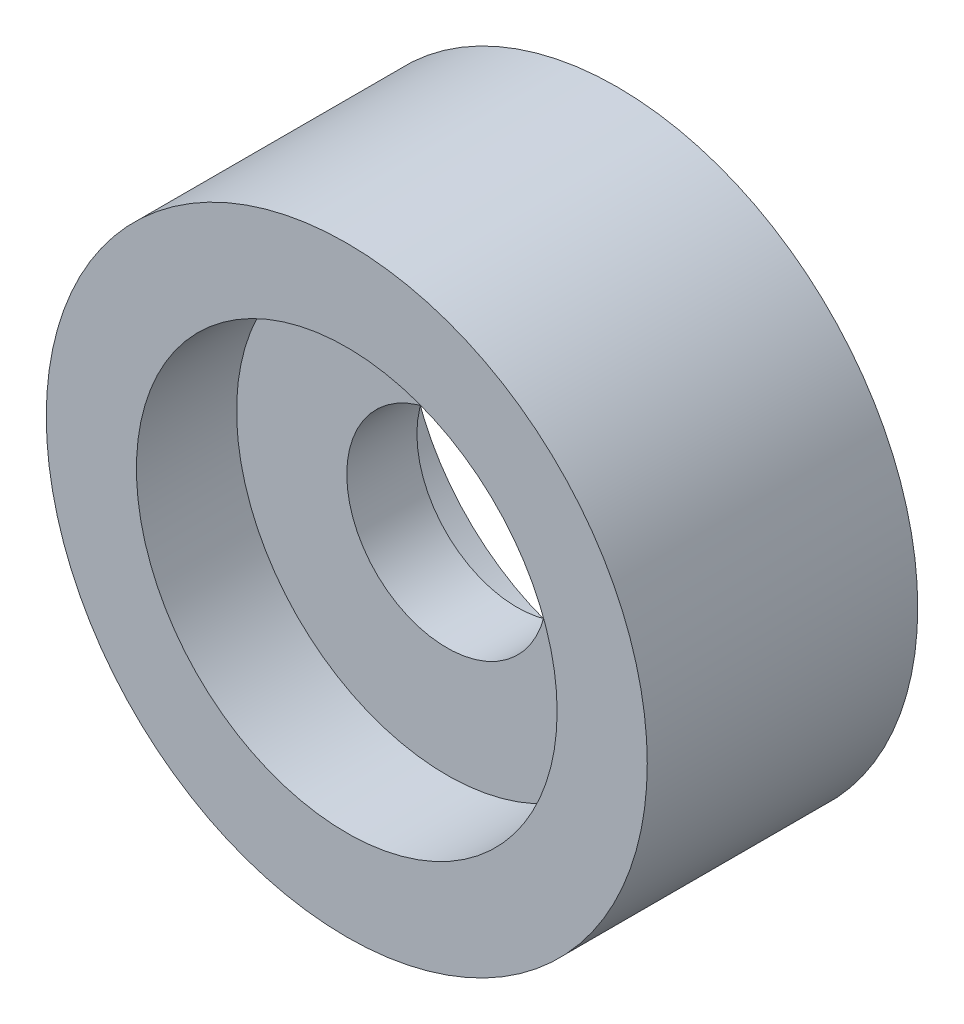
SolidWorks part; units mm, degrees
ref_plane "Plan de face" through (0, 0, 0) normal (0, 0, 1) x (1, 0, 0)
ref_plane "Plan de dessus" through (0, 0, 0) normal (0, 1, 0) x (1, 0, 0)
ref_plane "Plan de droite" through (0, 0, 0) normal (1, 0, 0) x (0, 0, -1)
sketch "Esquisse1" plane through (0, 0, 0) normal (0, 0, 1) x (1, 0, 0)
  circle A0 centre (0, 0) radius 30
  dimension "D1" = 60
extrude "Boss.-Extru.1" add sketch "Esquisse1" along normal blind 27
sketch "Esquisse3" plane through (0, 0, 27) normal (0, 0, 1) x (1, 0, 0)
  circle A0 centre (0, 0) radius 21
extrude "Enlèv. mat.-Extru.1" cut sketch "Esquisse3" against normal blind 10
sketch "Esquisse4" plane through (0, 0, 0) normal (0, 0, -1) x (-1, 0, 0)
  circle A0 centre (0, 0) radius 21
extrude "Enlèv. mat.-Extru.2" cut sketch "Esquisse4" against normal blind 10
sketch "Esquisse5" plane through (0, 0, 10) normal (0, 0, -1) x (-1, 0, 0)
  circle A0 centre (0, 0) radius 10
extrude "Enlèv. mat.-Extru.3" cut sketch "Esquisse5" against normal blind 10
